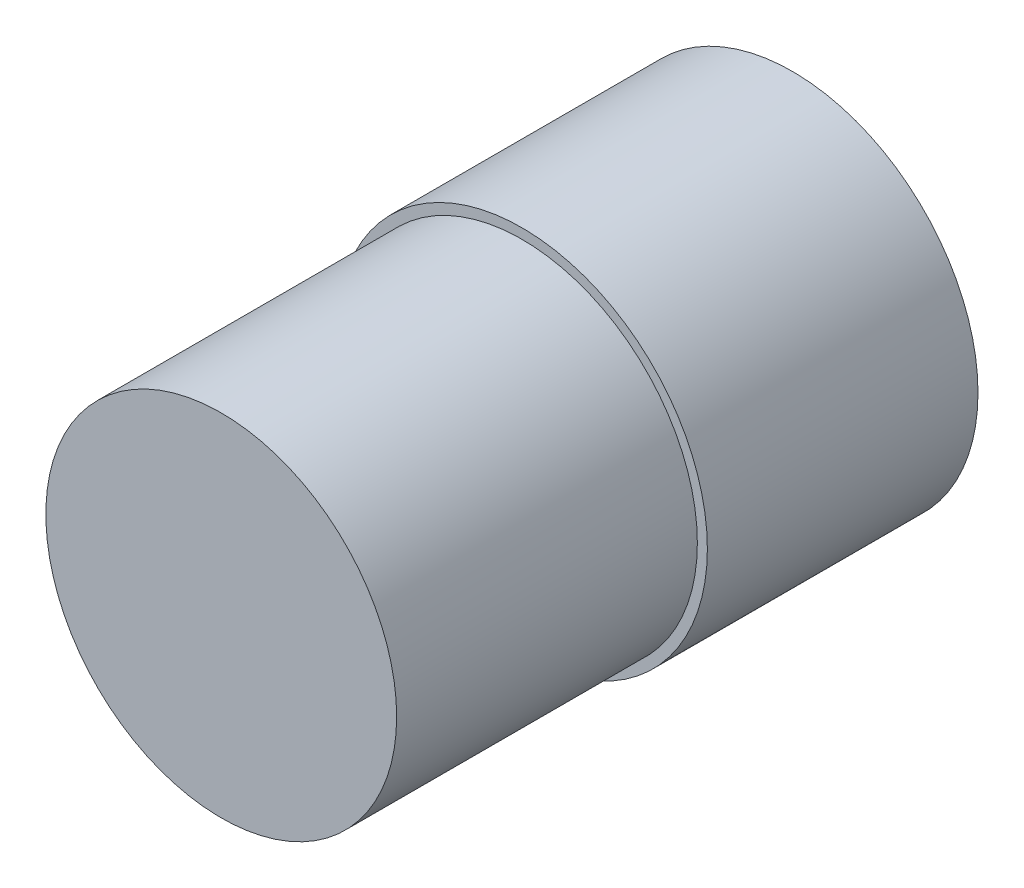
SolidWorks part; units mm, degrees
ref_plane "前视基准面" through (0, 0, 0) normal (0, 0, 1) x (1, 0, 0)
ref_plane "上视基准面" through (0, 0, 0) normal (0, 1, 0) x (1, 0, 0)
ref_plane "右视基准面" through (0, 0, 0) normal (1, 0, 0) x (0, 0, -1)
sketch "草图1" plane through (0, 0, 0) normal (0, 0, 1) x (1, 0, 0)
  circle A0 centre (0, 0) radius 18.5
extrude "凸台-拉伸1" add sketch "草图1" along normal blind 27
sketch "草图2" plane through (0, 0, 27) normal (0, 0, 1) x (1, 0, 0)
  circle A0 centre (0, 0) radius 17.5
extrude "凸台-拉伸2" add sketch "草图2" along normal blind 30
sketch "草图3" plane through (0, 0, 0) normal (0, 0, -1) x (-1, 0, 0)
  line L0 (-25.0267, 0) -> (24.5966, 0) construction
  line L1 (0, 20.0559) -> (0, -21.3049) construction
  circle A1 centre (0, -9.25) radius 2.75
  dimension "D1" = 9.25
extrude "切除-拉伸1" cut sketch "草图3" against normal blind 24.4
sketch "草图4" plane through (0, 0, 0) normal (0, 0, -1) x (-1, 0, 0)
  line L0 (0, 19.6716) -> (0, -19.1432) construction
  circle A0 centre (-16, -1.25) radius 1.6
  circle A1 centre (-8, 11.75) radius 1.6
  circle A2 centre (0, -9.25) radius 2.75 construction
  circle A3 centre (0, -9.25) radius 2.75
  circle A4 centre (16, -1.25) radius 1.6
  circle A5 centre (8, 11.75) radius 1.6
  dimension "D1" = 3.2
  dimension "D2" = 3.2
  dimension "D3" = 8
  dimension "D4" = 16
  dimension "D5" = 8
  dimension "D6" = 21
extrude "切除-拉伸2" cut sketch "草图4" against normal blind 10
